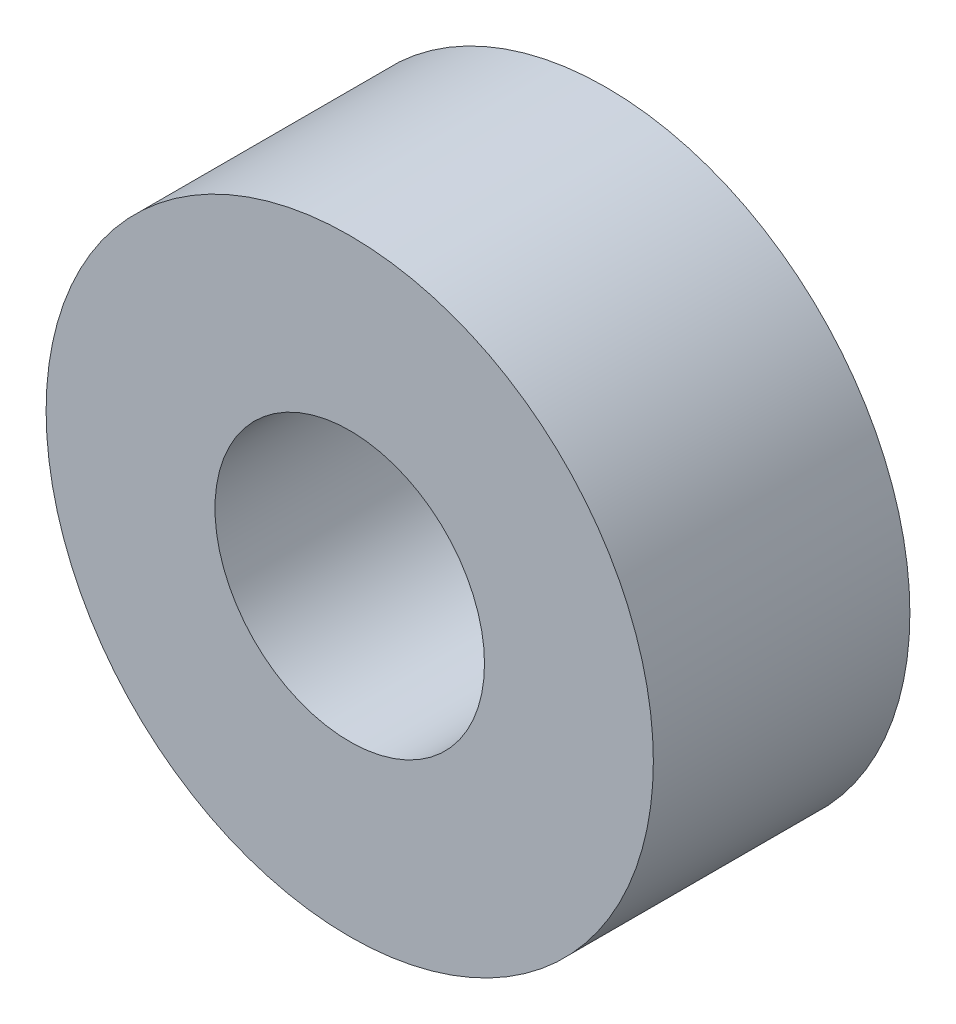
SolidWorks part; units mm, degrees
ref_plane "Front Plane" through (0, 0, 0) normal (0, 0, 1) x (1, 0, 0)
ref_plane "Top Plane" through (0, 0, 0) normal (0, 1, 0) x (1, 0, 0)
ref_plane "Right Plane" through (0, 0, 0) normal (1, 0, 0) x (0, 0, -1)
sketch "Sketch1" plane through (0, 0, 0) normal (0, 0, 1) x (1, 0, 0)
  circle A0 centre (0, 0) radius 9.35
  circle A1 centre (0, 0) radius 4.15
  dimension "D1" = 18.7
  dimension "D2" = 8.3
extrude "Boss-Extrude1" add sketch "Sketch1" along normal blind 7.9
